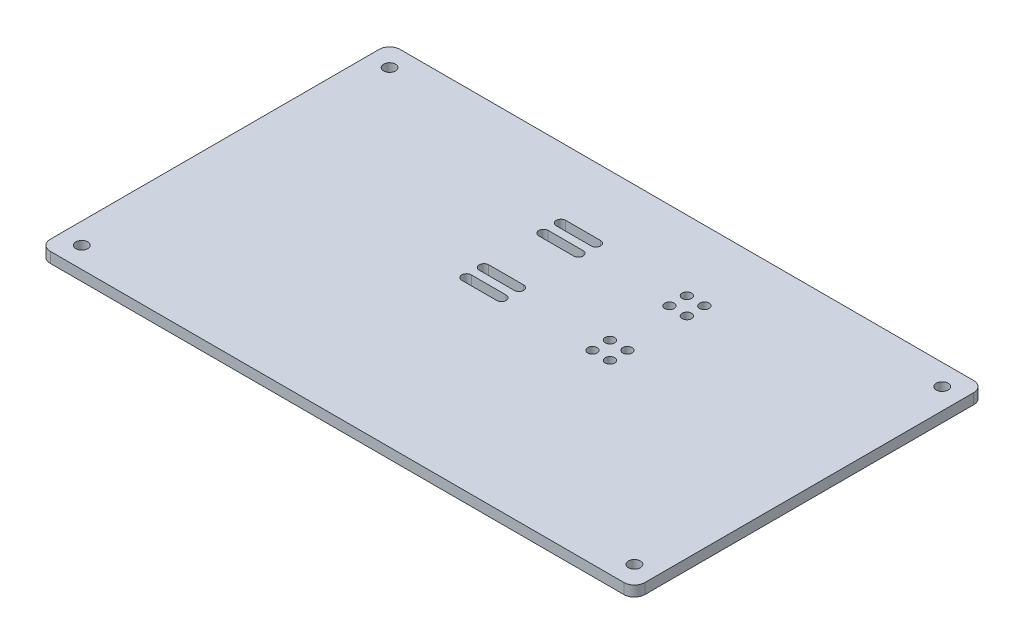
SolidWorks part; units mm, degrees
ref_plane "前视基准面" through (0, 0, 0) normal (0, 0, 1) x (1, 0, 0)
ref_plane "上视基准面" through (0, 0, 0) normal (0, 1, 0) x (1, 0, 0)
ref_plane "右视基准面" through (0, 0, 0) normal (1, 0, 0) x (0, 0, -1)
sketch "草图1" plane through (0, 0, 0) normal (0, 1, 0) x (1, 0, 0)
  line L0 (-85, 0) -> (85, 0) construction
  line L1 (-85, 50) -> (85, 50)
  line L2 (-85, 50) -> (-85, -50)
  line L3 (-85, -50) -> (85, -50)
  line L4 (85, 50) -> (85, -50)
  line L5 (-85, 50) -> (85, -50) construction
  line L6 (-85, -50) -> (85, 50) construction
  line L7 (0, -50) -> (0, 50) construction
  circle A0 centre (-79, -44) radius 1.7
  circle A1 centre (79, 44) radius 1.7
  circle A2 centre (79, -44) radius 1.7
  circle A132 centre (-79, 44) radius 1.7
  point P15 (-71, 36)
  dimension "D11" = 3.4
  dimension "D1" = 170
  dimension "D2" = 100
  dimension "D12" = 6
  dimension "D13" = 6
extrude "凸台-拉伸1" add sketch "草图1" along normal blind 3
sketch "草图2" plane through (0, 3, 0) normal (0, 1, 0) x (1, 0, 0)
  line L0 (0, 0) -> (85, 0) construction
  line L1 (85, -50) -> (85, 50) construction
  line L2 (-16, 26.35) -> (-6, 26.35)
  line L3 (-16, 31.35) -> (-6, 31.35)
  line L4 (-16, 23.65) -> (-6, 23.65)
  line L5 (-16, 28.65) -> (-6, 28.65)
  line L6 (-16, 26.35) -> (-6, 23.65) construction
  line L7 (-16, 31.35) -> (-6, 28.65) construction
  line L8 (-16, 28.65) -> (-6, 31.35) construction
  line L9 (-16, 23.65) -> (-6, 26.35) construction
  line L14 (-11, 30) -> (-11, 25) construction
  line L15 (-16, 4.35) -> (-6, 4.35)
  line L16 (-16, 9.35) -> (-6, 9.35)
  line L17 (-16, 1.65) -> (-6, 1.65)
  line L18 (-16, 6.65) -> (-6, 6.65)
  line L21 (-16, 4.35) -> (-6, 1.65) construction
  line L22 (-16, 9.35) -> (-6, 6.65) construction
  line L23 (-16, 6.65) -> (-6, 9.35) construction
  line L24 (-16, 1.65) -> (-6, 4.35) construction
  line L27 (-11, 8) -> (-11, 3) construction
  line L32 (-16, 21.35) -> (-6, 21.35) [skipped]
  line L33 (-16, 18.65) -> (-6, 18.65) [skipped]
  line L34 (-16, 21.35) -> (-6, 18.65) construction
  line L35 (-16, 18.65) -> (-6, 21.35) construction
  arc A0 (-6, 28.65) -> (-6, 31.35) centre (-6, 30) ccw
  arc A1 (-16, 31.35) -> (-16, 28.65) centre (-16, 30) ccw
  circle A2 centre (25, 30) radius 1.35
  circle A3 centre (20, 30) radius 1.35
  arc A5 (-6, 23.65) -> (-6, 26.35) centre (-6, 25) ccw
  arc A6 (-16, 26.35) -> (-16, 23.65) centre (-16, 25) ccw
  circle A7 centre (25, 25) radius 1.35
  circle A8 centre (20, 25) radius 1.35
  arc A15 (-6, 6.65) -> (-6, 9.35) centre (-6, 8) ccw
  arc A16 (-16, 9.35) -> (-16, 6.65) centre (-16, 8) ccw
  circle A17 centre (25, 8) radius 1.35
  circle A18 centre (20, 8) radius 1.35
  arc A20 (-6, 1.65) -> (-6, 4.35) centre (-6, 3) ccw
  arc A21 (-16, 4.35) -> (-16, 1.65) centre (-16, 3) ccw
  circle A22 centre (25, 3) radius 1.35
  circle A23 centre (20, 3) radius 1.35
  circle A31 centre (20, 20) radius 1.35 [skipped]
  circle A32 centre (25, 20) radius 1.35 [skipped]
  circle A34 centre (15, 30) radius 1.35 [skipped]
  arc A37 (-6, 18.65) -> (-6, 21.35) centre (-6, 20) ccw [skipped]
  arc A38 (-16, 21.35) -> (-16, 18.65) centre (-16, 20) ccw [skipped]
  point P5 (-11, 30)
  point P14 (-10, -8)
  point P17 (-11, 20)
  point P19 (-11, 25)
  point P47 (-11, 8)
  point P60 (-11, 3)
  dimension "D2" = 2.7
  dimension "D1" = 10
  dimension "D3" = 2.7
  dimension "D4" = 36
  dimension "D5" = 60
  dimension "D6" = 3
  dimension "D7" = 30
  dimension "D9" = 5
  dimension "D8" = 3
  dimension "D10" = 2
extrude "切除-拉伸1" cut sketch "草图2" against normal up to next
fillet "圆角1" radius 3 4 edges at (85, 1.5, -50) (85, 1.5, 50) (-85, 1.5, 50) (-85, 1.5, -50)
